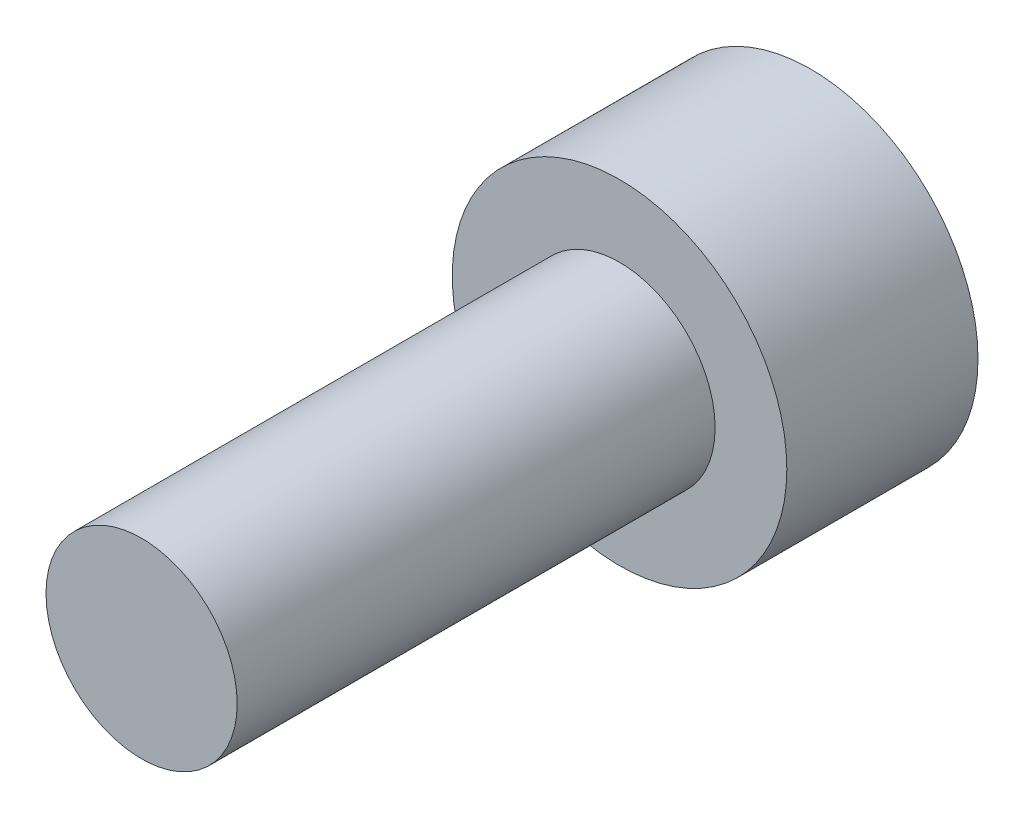
SolidWorks part; units mm, degrees
material "Acero aleado"
ref_plane "Alzado" through (0, 0, 0) normal (0, 0, 1) x (1, 0, 0)
ref_plane "Planta" through (0, 0, 0) normal (0, 1, 0) x (1, 0, 0)
ref_plane "Vista lateral" through (0, 0, 0) normal (1, 0, 0) x (0, 0, -1)
sketch "Croquis1" plane through (0, 0, 0) normal (0, 0, 1) x (1, 0, 0)
  circle A0 centre (0, 0) radius 3.5
  dimension "D1" = 7
extrude "Cabeza" add sketch "Croquis1" along normal blind 4 from offset 4
sketch "Croquis2" plane through (0, 0, 0) normal (0, 0, 1) x (1, 0, 0)
  circle A0 centre (0, 0) radius 2
  dimension "D1" = 4
extrude "Cuerpo" add sketch "Croquis2" along normal blind 10
sketch "Croquis3" plane through (0, 0, 0) normal (0, 0, 1) x (1, 0, 0)
  line L0 (1.7321, 0) -> (0.866, 1.5)
  line L1 (0.866, 1.5) -> (-0.866, 1.5)
  line L2 (-0.866, 1.5) -> (-1.7321, 0)
  line L3 (-1.7321, 0) -> (-0.866, -1.5)
  line L4 (-0.866, -1.5) -> (0.866, -1.5)
  line L5 (0.866, -1.5) -> (1.7321, 0)
  dimension "D1" = 1.7321
  dimension "D2" = 0.866
  dimension "D3" = 1.5
  dimension "D4" = 0.866
  dimension "D5" = 1.5
  dimension "D6" = 1.7321
  dimension "D7" = 0.866
  dimension "D8" = 1.5
  dimension "D9" = 0.866
  dimension "D10" = 1.5
extrude "Hexagono_interior" cut sketch "Croquis3" along normal blind 2 from offset 4
